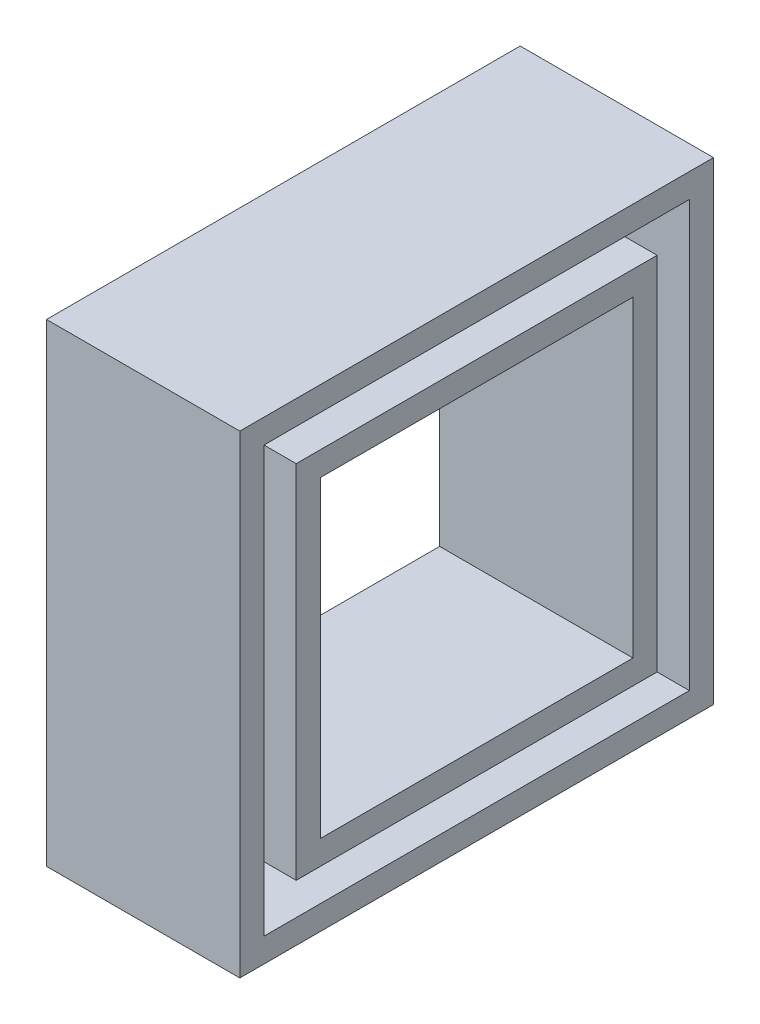
SolidWorks part; units mm, degrees
ref_plane "Alzado" through (0, 0, 0) normal (0, 0, 1) x (1, 0, 0)
ref_plane "Planta" through (0, 0, 0) normal (0, 1, 0) x (1, 0, 0)
ref_plane "Vista lateral" through (0, 0, 0) normal (1, 0, 0) x (0, 0, -1)
sketch "Croquis2" plane through (0, 0, 0) normal (1, 0, 0) x (0, 0, -1)
  line L0 (2, 2) -> (-27.4, 2)
  line L1 (0, 0) -> (-25.4, 0)
  line L2 (0, 0) -> (0, -25.4)
  line L3 (0, -25.4) -> (-25.4, -25.4)
  line L4 (-25.4, 0) -> (-25.4, -25.4)
  line L5 (-27.4, 2) -> (-27.4, -27.4)
  line L6 (2, -27.4) -> (-27.4, -27.4)
  line L7 (2, 2) -> (2, -27.4)
  line L8 (-1, -1) -> (-24.4, -1)
  line L9 (-24.4, -1) -> (-24.4, -24.4)
  line L10 (-1, -24.4) -> (-24.4, -24.4)
  line L11 (-1, -1) -> (-1, -24.4)
  line L12 (-3, -3) -> (-22.4, -3)
  line L13 (-22.4, -3) -> (-22.4, -22.4)
  line L14 (-3, -22.4) -> (-22.4, -22.4)
  line L15 (-3, -3) -> (-3, -22.4)
  dimension "D1" = 25.4
  dimension "D2" = 25.4
  dimension "D3" = 2
  dimension "D4" = 1
  dimension "D5" = 2
extrude "Saliente-Extruir1" add sketch "Croquis2" along normal blind 10 contours L11 L8 L9 L10 L12 L15 L14 L13 | L7 L0 L5 L6 L4 L1 L2 L3
sketch "Croquis3" plane through (0, 0, 0) normal (-1, 0, 0) x (0, 0, 1)
  line L1 (-2, 2) -> (27.4, 2)
  line L2 (-2, 2) -> (-2, -27.4)
  line L3 (-2, -27.4) -> (27.4, -27.4)
  line L4 (27.4, 2) -> (27.4, -27.4)
  line L5 (3, -3) -> (22.4, -3)
  line L6 (3, -3) -> (3, -22.4)
  line L7 (3, -22.4) -> (22.4, -22.4)
  line L8 (22.4, -3) -> (22.4, -22.4)
extrude "Saliente-Extruir2" add sketch "Croquis3" along normal blind 2
sketch "Croquis4" plane through (10, 0, 0) normal (1, 0, 0) x (0, 0, -1)
  line L0 (-25.9, 0.5) -> (-25.9, -25.9)
  line L1 (-24.4, -1) -> (-1, -1) construction
  line L2 (-24.4, -1) -> (-24.4, -24.4) construction
  line L3 (-24.4, -24.4) -> (-1, -24.4) construction
  line L4 (-1, -1) -> (-1, -24.4) construction
  line L5 (-25.4, 0) -> (0, 0) construction
  line L6 (-25.4, 0) -> (-25.4, -25.4) construction
  line L7 (-25.4, -25.4) -> (0, -25.4) construction
  line L8 (0, 0) -> (0, -25.4) construction
  line L9 (-25.9, -25.9) -> (0.5, -25.9)
  line L10 (0.5, 0.5) -> (0.5, -25.9)
  line L11 (-25.9, 0.5) -> (0.5, 0.5)
  line L12 (-23.9, -1.5) -> (-23.9, -23.9)
  line L13 (-23.9, -23.9) -> (-1.5, -23.9)
  line L14 (-1.5, -1.5) -> (-1.5, -23.9)
  line L15 (-23.9, -1.5) -> (-1.5, -1.5)
  dimension "D1" = 0.5
  dimension "D2" = 0.5
extrude "Cortar-Extruir1" cut sketch "Croquis4" against normal up to surface (10 mm away) up to face at (0, -12.7, 12.7)
